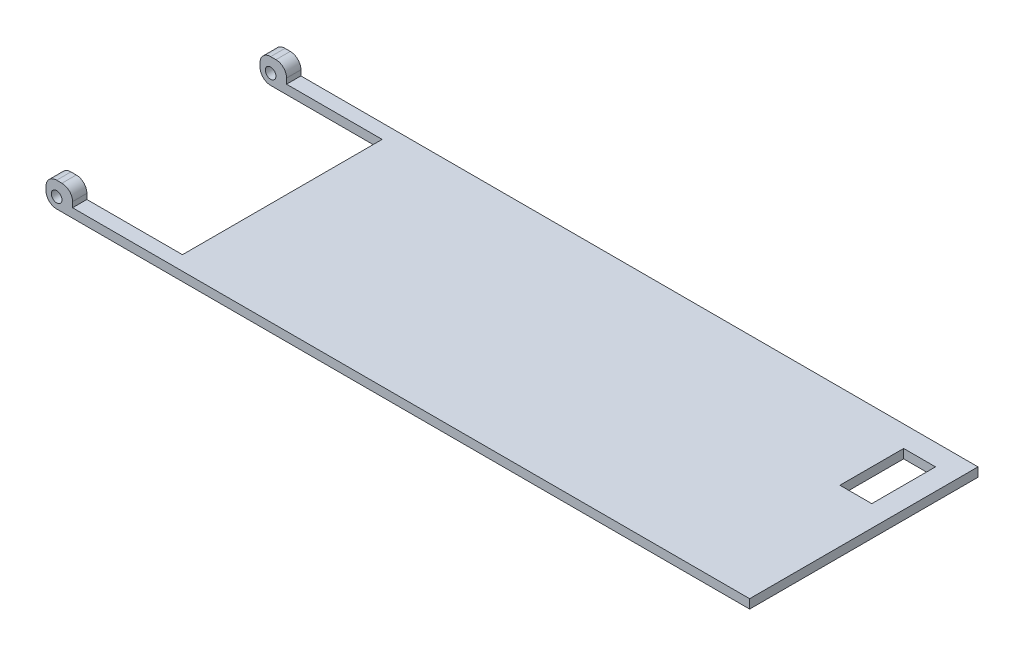
SolidWorks part; units mm, degrees
ref_plane "Front Plane" through (0, 0, 0) normal (0, 0, 1) x (1, 0, 0)
ref_plane "Top Plane" through (0, 0, 0) normal (0, 1, 0) x (1, 0, 0)
ref_plane "Right Plane" through (0, 0, 0) normal (1, 0, 0) x (0, 0, -1)
sketch "Sketch1" plane through (0, 0, 0) normal (0, 1, 0) x (1, 0, 0)
  line L1 (-66.25, -21.5) -> (66.25, -21.5)
  line L2 (-66.25, -21.5) -> (-66.25, 21.5)
  line L3 (-66.25, 21.5) -> (66.25, 21.5)
  line L4 (66.25, -21.5) -> (66.25, 21.5)
  line L5 (-66.25, -21.5) -> (66.25, 21.5) construction
  line L6 (-66.25, 21.5) -> (66.25, -21.5) construction
  point P0 (0, 0)
  dimension "D1" = 132.5
  dimension "D2" = 43
extrude "Boss-Extrude1" add sketch "Sketch1" along normal blind 1.7
sketch "Sketch2" plane through (0, 1.7, 0) normal (0, 1, 0) x (1, 0, 0)
  line L0 (-66.25, 21.5) -> (-66.25, -21.5) construction
  line L1 (-66.25, -18.8) -> (-43.25, -18.8)
  line L2 (-66.25, -18.8) -> (-66.25, 18.8)
  line L3 (-66.25, 18.8) -> (-43.25, 18.8)
  line L4 (-43.25, -18.8) -> (-43.25, 18.8)
  line L5 (-66.25, -21.5) -> (66.25, -21.5) construction
  line L6 (66.25, 21.5) -> (-66.25, 21.5) construction
  dimension "D1" = 2.7
  dimension "D2" = 2.7
  dimension "D3" = 23
extrude "Cut-Extrude1" cut sketch "Sketch2" against normal up to vertex (1.7 mm away)
sketch "Sketch4" plane through (0, 1.7, 0) normal (0, 1, 0) x (1, 0, 0)
  line L0 (-66.25, -21.5) -> (66.25, -21.5) construction
  line L1 (-66.25, -18.8) -> (-61.25, -18.8)
  line L2 (-66.25, -18.8) -> (-66.25, -21.5)
  line L3 (-66.25, -21.5) -> (-61.25, -21.5)
  line L4 (-61.25, -18.8) -> (-61.25, -21.5)
  dimension "D1" = 5
extrude "Boss-Extrude2" add sketch "Sketch4" along normal blind 3
sketch "Sketch5" plane through (0, 0, 21.5) normal (0, 0, 1) x (1, 0, 0)
  line L0 (-66.25, 0) -> (66.25, 0) construction
  line L1 (-66.25, 4.7) -> (-66.25, 0) construction
  circle A0 centre (-64.25, 2) radius 1
  dimension "D3" = 2
  dimension "D1" = 2
  dimension "D2" = 2
extrude "Cut-Extrude2" cut sketch "Sketch5" against normal up to vertex (2.7 mm away) contours A0
fillet "Fillet1" radius 2 3 edges at (-66.25, 0, 20.15) (-66.25, 4.7, 20.15) (-61.25, 4.7, 20.15)
ref_plane "Plane1" through (0, 0, 0) normal (0, 0, 1) x (1, 0, 0)
mirror "Mirror2" about plane through (0, 0, 0) normal (0, 0, 1) of "Boss-Extrude2", "Cut-Extrude2", "Fillet1"
sketch "Sketch10" plane through (0, 1.7, 0) normal (0, 1, 0) x (1, 0, 0)
  line L0 (66.25, -21.5) -> (66.25, 21.5) construction
  line L1 (56.25, 5.5) -> (62.25, 5.5)
  line L2 (56.25, 5.5) -> (56.25, 17.5)
  line L3 (56.25, 17.5) -> (62.25, 17.5)
  line L4 (62.25, 5.5) -> (62.25, 17.5)
  line L5 (56.25, 5.5) -> (62.25, 17.5) construction
  line L6 (56.25, 17.5) -> (62.25, 5.5) construction
  line L7 (66.25, 21.5) -> (-61.25, 21.5) construction
  point P0 (59.25, 11.5)
  dimension "D1" = 4
  dimension "D2" = 6
  dimension "D3" = 4
  dimension "D4" = 12
extrude "Cut-Extrude3" cut sketch "Sketch10" against normal up to vertex (1.7 mm away) up to point (66.25, 0, -21.5)
